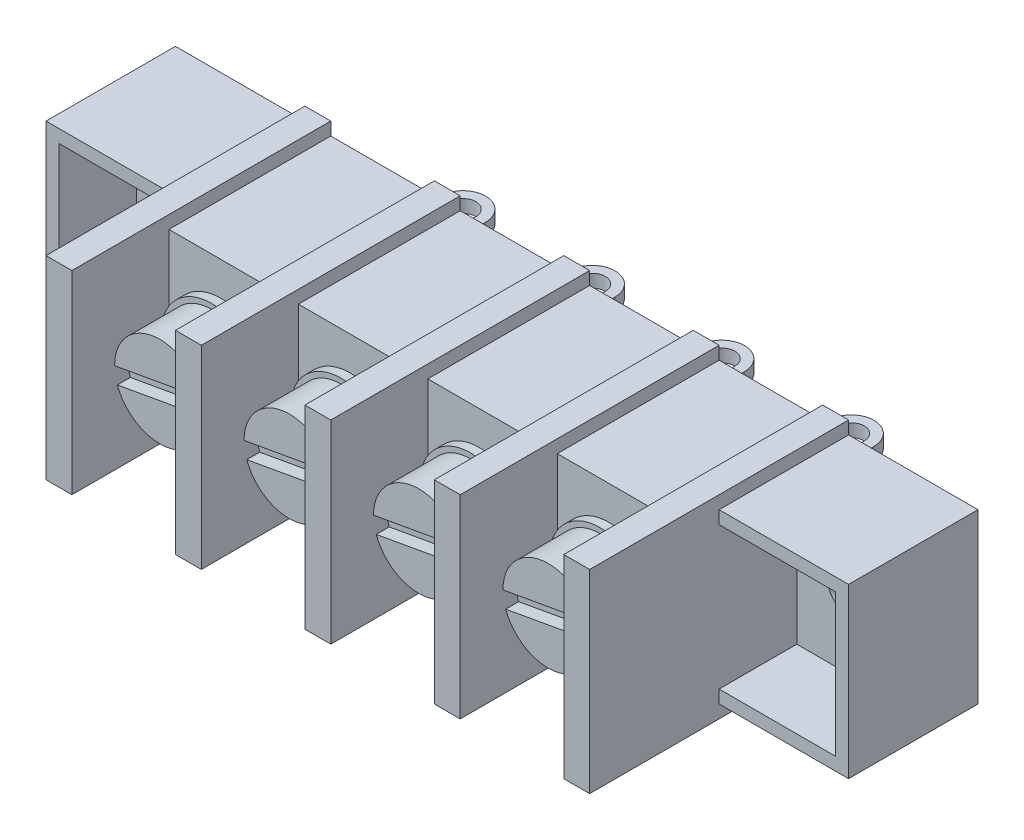
SolidWorks part; units mm, degrees
ref_plane "Спереди" through (0, 0, 0) normal (0, 0, 1) x (1, 0, 0)
ref_plane "Сверху" through (0, 0, 0) normal (0, 1, 0) x (1, 0, 0)
ref_plane "Справа" through (0, 0, 0) normal (1, 0, 0) x (0, 0, -1)
sketch "Эскиз1" plane through (0, 0, 0) normal (0, 0, 1) x (1, 0, 0)
  line L0 (-47.9787, 0) -> (44.4324, 0) construction
  line L1 (0, 0) -> (0, 38.9044) construction
  line L2 (-41, -7.5) -> (41, -7.5)
  line L3 (-41, -7.5) -> (-41, 7.5)
  line L4 (-41, 7.5) -> (41, 7.5)
  line L5 (41, -7.5) -> (41, 7.5)
  dimension "D1" = 15
  dimension "D2" = 82
extrude "Вытянуть1" add sketch "Эскиз1" along normal blind 10
sketch "Эскиз2" plane through (0, 0, 10) normal (0, 0, 1) x (1, 0, 0)
  line L0 (41, 7.5) -> (-41, 7.5) construction
  line L1 (-41, -7.5) -> (-39, -7.5)
  line L2 (-41, -7.5) -> (-41, 7.5)
  line L3 (-41, 7.5) -> (-39, 7.5)
  line L4 (-39, -7.5) -> (-39, 7.5)
  line L5 (0, 13.212) -> (0, -10.8914) construction
  line L6 (-41, -7.5) -> (41, -7.5) construction
  line L7 (-31, -7.5) -> (-29, -7.5)
  line L8 (-31, -7.5) -> (-31, 7.5)
  line L9 (-31, 7.5) -> (-29, 7.5)
  line L10 (-29, -7.5) -> (-29, 7.5)
  line L11 (-30, 8.3866) -> (-30, -8.2377) construction
  line L12 (1, 7.5) -> (-1, 7.5)
  line L13 (1, -7.5) -> (1, 7.5)
  line L14 (1, -7.5) -> (-1, -7.5)
  line L15 (-1, -7.5) -> (-1, 7.5)
  line L16 (29, -7.5) -> (29, 7.5)
  line L17 (31, 7.5) -> (29, 7.5)
  line L18 (31, -7.5) -> (31, 7.5)
  line L19 (31, -7.5) -> (29, -7.5)
  line L20 (39, -7.5) -> (39, 7.5)
  line L21 (41, 7.5) -> (39, 7.5)
  line L22 (41, -7.5) -> (41, 7.5)
  line L23 (41, -7.5) -> (39, -7.5)
  line L24 (-21, -7.5) -> (-19, -7.5)
  line L25 (-21, -7.5) -> (-21, 7.5)
  line L26 (-21, 7.5) -> (-19, 7.5)
  line L27 (-19, -7.5) -> (-19, 7.5)
  line L28 (9, -7.5) -> (9, 7.5)
  line L29 (-11, -7.5) -> (-9, -7.5)
  line L30 (-11, -7.5) -> (-11, 7.5)
  line L31 (-11, 7.5) -> (-9, 7.5)
  line L32 (-9, -7.5) -> (-9, 7.5)
  line L33 (11, 7.5) -> (9, 7.5)
  line L34 (-10, 8.3866) -> (-10, -8.2377) construction
  line L35 (-20, 8.3866) -> (-20, -8.2377) construction
  line L36 (11, -7.5) -> (11, 7.5)
  line L37 (11, -7.5) -> (9, -7.5)
  line L38 (19, -7.5) -> (19, 7.5)
  line L39 (21, 7.5) -> (19, 7.5)
  line L40 (21, -7.5) -> (21, 7.5)
  line L41 (21, -7.5) -> (19, -7.5)
  dimension "D1" = 2
  dimension "D2" = 10
  dimension "D3" = 2
  dimension "D4" = 8
extrude "Вытянуть2" add sketch "Эскиз2" along normal blind 10
sketch "Эскиз3" plane through (0, 0, 10) normal (0, 0, 1) x (1, 0, 0)
  line L0 (-35, 10.8914) -> (-35, -9.6255) construction
  line L3 (-31, 7.5) -> (-31, -7.5) construction
  line L4 (-39, -7.5) -> (-39, 7.5) construction
  line L5 (-39, -7.5) -> (-31, -7.5) construction
  line L6 (-39, -7.5) -> (-31, -7.5)
  line L7 (-39, -7.5) -> (-39, 7.5)
  line L8 (-39, 7.5) -> (-31, 7.5)
  line L9 (-31, -7.5) -> (-31, 7.5)
  line L10 (-31, 7.5) -> (-39, 7.5) construction
  line L13 (-21, -7.5) -> (-21, 7.5)
  line L14 (-21, 7.5) -> (-29, 7.5)
  line L15 (-21, -7.5) -> (-21, 7.5)
  line L16 (-29, -7.5) -> (-21, -7.5)
  line L17 (-29, 7.5) -> (-29, -7.5)
  line L18 (-21, 7.5) -> (-29, 7.5)
  line L19 (-29, 7.5) -> (-29, -7.5)
  line L20 (-29, -7.5) -> (-21, -7.5)
  line L25 (-11, -7.5) -> (-11, 7.5)
  line L26 (-11, 7.5) -> (-19, 7.5)
  line L27 (-19, 7.5) -> (-19, -7.5)
  line L28 (-19, -7.5) -> (-11, -7.5)
  line L33 (-9, 7.5) -> (-9, -7.5)
  line L34 (-9, -7.5) -> (-1, -7.5)
  line L35 (-1, -7.5) -> (-1, 7.5)
  line L36 (-1, 7.5) -> (-9, 7.5)
  line L42 (9, -7.5) -> (9, 7.5)
  line L43 (9, 7.5) -> (1, 7.5)
  line L44 (1, 7.5) -> (1, -7.5)
  line L45 (1, -7.5) -> (9, -7.5)
  line L50 (19, -7.5) -> (19, 7.5)
  line L51 (19, 7.5) -> (11, 7.5)
  line L52 (11, 7.5) -> (11, -7.5)
  line L53 (11, -7.5) -> (19, -7.5)
  line L58 (21, 7.5) -> (21, -7.5)
  line L59 (21, -7.5) -> (29, -7.5)
  line L60 (29, -7.5) -> (29, 7.5)
  line L61 (29, 7.5) -> (21, 7.5)
  line L66 (39, -7.5) -> (39, 7.5)
  line L67 (39, 7.5) -> (31, 7.5)
  line L68 (31, 7.5) -> (31, -7.5)
  line L69 (31, -7.5) -> (39, -7.5)
  dimension "D1" = 8
  dimension "D2" = 0
extrude "Вытянуть3" add sketch "Эскиз3" along normal blind 2.5
sketch "Эскиз4" plane through (0, 0, 12.5) normal (0, 0, 1) x (1, 0, 0)
  line L0 (-24.2616, 0) -> (23.4177, 0) construction
  line L1 (-35, 0) -> (-35, 16.4068) construction
  line L4 (0, 0) -> (0, 14.617) construction
  line L6 (-39, -7.5) -> (-39, 7.5) construction
  line L7 (-31, -7.5) -> (-31, 7.5) construction
  circle A0 centre (-35, 0) radius 3.9
  circle A1 centre (-25, 0) radius 3.9
  circle A2 centre (-15, 0) radius 3.9
  circle A3 centre (-5, 0) radius 3.9
  circle A4 centre (5, 0) radius 3.9
  circle A5 centre (15, 0) radius 3.9
  circle A6 centre (25, 0) radius 3.9
  circle A7 centre (35, 0) radius 3.9
  dimension "D1" = 7.8
  dimension "D2" = 10
extrude "Вытянуть4" add sketch "Эскиз4" along normal blind 0.7
sketch "Эскиз6" plane through (0, 0, 13.2) normal (0, 0, 1) x (1, 0, 0)
  line L0 (0, 0) -> (0, 15.7615) construction
  circle A0 centre (-35, 0) radius 3.5
  circle A1 centre (-35, 0) radius 3.9 construction
  circle A2 centre (-25, 0) radius 3.5
  circle A3 centre (-15, 0) radius 3.5
  circle A4 centre (-5, 0) radius 3.5
  circle A5 centre (5, 0) radius 3.5
  circle A6 centre (15, 0) radius 3.5
  circle A7 centre (25, 0) radius 3.5
  circle A8 centre (35, 0) radius 3.5
  circle A11 centre (5, 0) radius 3.5 [skipped]
  circle A12 centre (15, 0) radius 3.5 [skipped]
  circle A13 centre (25, 0) radius 3.5 [skipped]
  circle A14 centre (35, 0) radius 3.5 [skipped]
  dimension "D1" = 7
  dimension "D2" = 10
extrude "Вытянуть5" add sketch "Эскиз6" along normal blind 4
sketch "Эскиз7" plane through (0, 0, 17.2) normal (0, 0, 1) x (1, 0, 0)
  line L0 (-35, 0) -> (-19.4589, -11.6177) construction
  line L1 (-35, 0) -> (-12.9483, 3.9455) construction
  line L2 (-31.7114, 1.1979) -> (-38.5, -0.0167)
  line L3 (-31.5, 0.0167) -> (-38.2886, -1.1979)
  line L4 (-21.7114, 1.1979) -> (-28.5, -0.0167)
  line L5 (-21.5, 0.0167) -> (-28.2886, -1.1979)
  line L6 (-11.7114, 1.1979) -> (-18.5, -0.0167)
  line L7 (-11.5, 0.0167) -> (-18.2886, -1.1979)
  line L8 (-1.7114, 1.1979) -> (-8.5, -0.0167)
  line L9 (-1.5, 0.0167) -> (-8.2886, -1.1979)
  line L10 (0, 0) -> (0, 13.7349) construction
  line L11 (8.2886, 1.1979) -> (1.5, -0.0167)
  line L12 (8.5, 0.0167) -> (1.7114, -1.1979)
  line L13 (18.2886, 1.1979) -> (11.5, -0.0167)
  line L14 (18.5, 0.0167) -> (11.7114, -1.1979)
  line L15 (28.2886, 1.1979) -> (21.5, -0.0167)
  line L16 (28.5, 0.0167) -> (21.7114, -1.1979)
  line L17 (38.2886, 1.1979) -> (31.5, -0.0167)
  line L18 (38.5, 0.0167) -> (31.7114, -1.1979)
  circle A0 centre (-35, 0) radius 3.5 construction
  arc A1 (-31.5, 0.0167) -> (-31.7114, 1.1979) centre (-35, 0) ccw
  arc A2 (-38.5, -0.0167) -> (-38.2886, -1.1979) centre (-35, 0) ccw
  arc A3 (-21.5, 0.0167) -> (-21.7114, 1.1979) centre (-25, 0) ccw
  arc A4 (-28.5, -0.0167) -> (-28.2886, -1.1979) centre (-25, 0) ccw
  arc A5 (-11.5, 0.0167) -> (-11.7114, 1.1979) centre (-15, 0) ccw
  arc A6 (-18.5, -0.0167) -> (-18.2886, -1.1979) centre (-15, 0) ccw
  arc A7 (-1.5, 0.0167) -> (-1.7114, 1.1979) centre (-5, 0) ccw
  arc A8 (-8.5, -0.0167) -> (-8.2886, -1.1979) centre (-5, 0) ccw
  arc A9 (8.5, 0.0167) -> (8.2886, 1.1979) centre (5, 0) ccw
  arc A10 (1.5, -0.0167) -> (1.7114, -1.1979) centre (5, 0) ccw
  arc A11 (18.5, 0.0167) -> (18.2886, 1.1979) centre (15, 0) ccw
  arc A12 (11.5, -0.0167) -> (11.7114, -1.1979) centre (15, 0) ccw
  arc A13 (28.5, 0.0167) -> (28.2886, 1.1979) centre (25, 0) ccw
  arc A14 (21.5, -0.0167) -> (21.7114, -1.1979) centre (25, 0) ccw
  arc A15 (38.5, 0.0167) -> (38.2886, 1.1979) centre (35, 0) ccw
  arc A16 (31.5, -0.0167) -> (31.7114, -1.1979) centre (35, 0) ccw
  dimension "D2" = 1.2
extrude "Вырез-Вытянуть1" cut sketch "Эскиз7" against normal blind 1
sketch "Эскиз8" plane through (0, 0, 0) normal (0, 0, -1) x (-1, 0, 0)
  line L0 (-23.7342, 0) -> (23.7342, 0) construction
  line L1 (0, 12.8956) -> (0, -12.4209) construction
  line L2 (23.25, -0.5) -> (26.75, -0.5)
  line L3 (23.25, -0.5) -> (23.25, 0.5)
  line L4 (23.25, 0.5) -> (26.75, 0.5)
  line L5 (26.75, -0.5) -> (26.75, 0.5)
  line L6 (13.25, -0.5) -> (16.75, -0.5)
  line L7 (13.25, -0.5) -> (13.25, 0.5)
  line L8 (13.25, 0.5) -> (16.75, 0.5)
  line L9 (16.75, -0.5) -> (16.75, 0.5)
  line L10 (3.25, -0.5) -> (6.75, -0.5)
  line L11 (3.25, -0.5) -> (3.25, 0.5)
  line L12 (3.25, 0.5) -> (6.75, 0.5)
  line L13 (6.75, -0.5) -> (6.75, 0.5)
  line L14 (-6.75, -0.5) -> (-3.25, -0.5)
  line L15 (-6.75, -0.5) -> (-6.75, 0.5)
  line L16 (-6.75, 0.5) -> (-3.25, 0.5)
  line L17 (-3.25, -0.5) -> (-3.25, 0.5)
  line L18 (-16.75, -0.5) -> (-13.25, -0.5)
  line L19 (-16.75, -0.5) -> (-16.75, 0.5)
  line L20 (-16.75, 0.5) -> (-13.25, 0.5)
  line L21 (-13.25, -0.5) -> (-13.25, 0.5)
  line L22 (-26.75, -0.5) -> (-23.25, -0.5)
  line L23 (-26.75, -0.5) -> (-26.75, 0.5)
  line L24 (-26.75, 0.5) -> (-23.25, 0.5)
  line L25 (-23.25, -0.5) -> (-23.25, 0.5)
  line L26 (-36.75, -0.5) -> (-33.25, -0.5)
  line L27 (-36.75, -0.5) -> (-36.75, 0.5)
  line L28 (-36.75, 0.5) -> (-33.25, 0.5)
  line L29 (-33.25, -0.5) -> (-33.25, 0.5)
  line L47 (33.25, -0.5) -> (36.75, -0.5)
  line L48 (33.25, -0.5) -> (33.25, 0.5)
  line L49 (33.25, 0.5) -> (36.75, 0.5)
  line L50 (36.75, -0.5) -> (36.75, 0.5)
extrude "Вытянуть6" add sketch "Эскиз8" along normal blind 8
sketch "Эскиз10" plane through (-41, 0, 0) normal (-1, 0, 0) x (0, 0, 1)
  line L0 (10, -7.5) -> (10, 7.5)
  line L4 (0, 7.5) -> (0, -7.5)
  line L5 (0, -7.5) -> (20, -7.5)
  line L6 (20, -7.5) -> (20, 7.5)
  line L7 (20, 7.5) -> (0, 7.5)
  line L8 (0, 7.5) -> (0, -7.5)
  line L9 (0, -7.5) -> (10, -7.5)
  line L11 (10, 7.5) -> (0, 7.5)
  dimension "D2" = 10
  dimension "D1" = 0
extrude "Вытянуть7" add sketch "Эскиз10" along normal blind 10
sketch "Эскиз11" plane through (41, 0, 0) normal (1, 0, 0) x (0, 0, -1)
  line L4 (0, 7.5) -> (-10, 7.5)
  line L5 (0, -7.5) -> (0, 7.5)
  line L6 (-10, -7.5) -> (0, -7.5)
  line L7 (-10, 7.5) -> (-10, -7.5)
  line L8 (0, 7.5) -> (-10, 7.5)
  line L9 (0, -7.5) -> (0, 7.5)
  line L10 (-10, -7.5) -> (0, -7.5)
  line L11 (-10, 7.5) -> (-10, -7.5)
  dimension "D1" = 0
extrude "Вытянуть8" add sketch "Эскиз11" along normal blind 10
sketch "Эскиз12" plane through (0, 0, 10) normal (0, 0, 1) x (1, 0, 0)
  line L0 (-54.3833, 0) -> (55.0396, 0) construction
  line L1 (0, 0) -> (0, 16.7838) construction
  circle A0 centre (45, 0) radius 1.6
  circle A1 centre (-45, 0) radius 1.6
  dimension "D1" = 3.2
  dimension "D2" = 45
extrude "Вырез-Вытянуть2" cut sketch "Эскиз12" against normal blind 10
sketch "Эскиз13" plane through (0, 0, 10) normal (0, 0, 1) x (1, 0, 0)
  line L0 (41, 7.5) -> (41, -7.5) construction
  line L1 (41, -5.5) -> (50, -5.5)
  line L2 (41, -5.5) -> (41, 5.5)
  line L3 (41, 5.5) -> (50, 5.5)
  line L4 (50, -5.5) -> (50, 5.5)
  line L5 (51, 7.5) -> (51, -7.5) construction
  line L6 (51, 7.5) -> (41, 7.5) construction
  line L7 (51, -7.5) -> (41, -7.5) construction
  line L8 (0, 0) -> (0, 15.322) construction
  line L9 (-50, -5.5) -> (-50, 5.5)
  line L10 (-41, 5.5) -> (-50, 5.5)
  line L11 (-41, -5.5) -> (-41, 5.5)
  line L12 (-41, -5.5) -> (-50, -5.5)
  dimension "D1" = 1
  dimension "D2" = 2
  dimension "D3" = 2
extrude "Вырез-Вытянуть3" cut sketch "Эскиз13" against normal blind 6
sketch "Эскиз14" plane through (0, 0, 12.5) normal (0, 0, 1) x (1, 0, 0)
  line L0 (0, 0) -> (64.3223, 0) construction
  line L1 (0, 0) -> (0, 17.1529) construction
  line L2 (39, 7.5) -> (39, -7.5) construction
  line L3 (31, 7.5) -> (39, 7.5)
  line L4 (31, 7.5) -> (31, 6.5)
  line L5 (31, 6.5) -> (39, 6.5)
  line L6 (39, 7.5) -> (39, 6.5)
  line L7 (41, 7.5) -> (41, 5.5) construction
  line L8 (41, 6.5) -> (51, 6.5)
  line L9 (41, 6.5) -> (41, 7.5)
  line L10 (41, 7.5) -> (51, 7.5)
  line L11 (51, 6.5) -> (51, 7.5)
  line L12 (51, -6.5) -> (51, -7.5)
  line L13 (41, -7.5) -> (51, -7.5)
  line L14 (41, -6.5) -> (41, -7.5)
  line L15 (41, -6.5) -> (51, -6.5)
  line L16 (39, -7.5) -> (39, -6.5)
  line L17 (31, -6.5) -> (39, -6.5)
  line L18 (31, -7.5) -> (31, -6.5)
  line L19 (31, -7.5) -> (39, -7.5)
  line L20 (21, 7.5) -> (29, 7.5)
  line L21 (21, 7.5) -> (21, 6.5)
  line L22 (21, 6.5) -> (29, 6.5)
  line L23 (29, 7.5) -> (29, 6.5)
  line L24 (29, -7.5) -> (29, -6.5)
  line L25 (21, -6.5) -> (29, -6.5)
  line L26 (21, -7.5) -> (21, -6.5)
  line L27 (21, -7.5) -> (29, -7.5)
  line L28 (11, 7.5) -> (19, 7.5)
  line L29 (11, 7.5) -> (11, 6.5)
  line L30 (11, 6.5) -> (19, 6.5)
  line L31 (19, 7.5) -> (19, 6.5)
  line L32 (19, -7.5) -> (19, -6.5)
  line L33 (11, -6.5) -> (19, -6.5)
  line L34 (11, -7.5) -> (11, -6.5)
  line L35 (11, -7.5) -> (19, -7.5)
  line L36 (1, 7.5) -> (9, 7.5)
  line L37 (1, 7.5) -> (1, 6.5)
  line L38 (1, 6.5) -> (9, 6.5)
  line L39 (9, 7.5) -> (9, 6.5)
  line L40 (9, -7.5) -> (9, -6.5)
  line L41 (1, -6.5) -> (9, -6.5)
  line L42 (1, -7.5) -> (1, -6.5)
  line L43 (1, -7.5) -> (9, -7.5)
  line L44 (-9, 7.5) -> (-1, 7.5)
  line L45 (-9, 7.5) -> (-9, 6.5)
  line L46 (-9, 6.5) -> (-1, 6.5)
  line L47 (-1, 7.5) -> (-1, 6.5)
  line L48 (-1, -7.5) -> (-1, -6.5)
  line L49 (-9, -6.5) -> (-1, -6.5)
  line L50 (-9, -7.5) -> (-9, -6.5)
  line L51 (-9, -7.5) -> (-1, -7.5)
  line L52 (-19, 7.5) -> (-11, 7.5)
  line L53 (-19, 7.5) -> (-19, 6.5)
  line L54 (-19, 6.5) -> (-11, 6.5)
  line L55 (-11, 7.5) -> (-11, 6.5)
  line L56 (-11, -7.5) -> (-11, -6.5)
  line L57 (-19, -6.5) -> (-11, -6.5)
  line L58 (-19, -7.5) -> (-19, -6.5)
  line L59 (-19, -7.5) -> (-11, -7.5)
  line L60 (-29, 7.5) -> (-21, 7.5)
  line L61 (-29, 7.5) -> (-29, 6.5)
  line L62 (-29, 6.5) -> (-21, 6.5)
  line L63 (-21, 7.5) -> (-21, 6.5)
  line L64 (-21, -7.5) -> (-21, -6.5)
  line L65 (-29, -6.5) -> (-21, -6.5)
  line L66 (-29, -7.5) -> (-29, -6.5)
  line L67 (-29, -7.5) -> (-21, -7.5)
  line L68 (-39, 7.5) -> (-31, 7.5)
  line L69 (-39, 7.5) -> (-39, 6.5)
  line L70 (-39, 6.5) -> (-31, 6.5)
  line L71 (-31, 7.5) -> (-31, 6.5)
  line L72 (-31, -7.5) -> (-31, -6.5)
  line L73 (-39, -6.5) -> (-31, -6.5)
  line L74 (-39, -7.5) -> (-39, -6.5)
  line L75 (-39, -7.5) -> (-31, -7.5)
  line L76 (-41, -6.5) -> (-51, -6.5)
  line L77 (-41, -6.5) -> (-41, -7.5)
  line L78 (-41, -7.5) -> (-51, -7.5)
  line L79 (-51, -6.5) -> (-51, -7.5)
  line L80 (-51, 6.5) -> (-51, 7.5)
  line L81 (-41, 7.5) -> (-51, 7.5)
  line L82 (-41, 6.5) -> (-41, 7.5)
  line L83 (-41, 6.5) -> (-51, 6.5)
  dimension "D1" = 1
extrude "Вырез-Вытянуть4" cut sketch "Эскиз14" against normal blind 20
sketch "Эскиз15" plane through (0, -0.5, 0) normal (0, -1, 0) x (1, 0, 0)
  line L0 (33.25, -6.2124) -> (33.25, -10.5448)
  line L3 (33.25, -8) -> (33.25, 0) construction
  line L4 (33.25, -10.5448) -> (36.75, -10.5448)
  line L5 (34, -6.2124) -> (34, -5.8124)
  line L6 (36, -6.2124) -> (36, -5.8124)
  line L7 (36.75, -6.2124) -> (36.75, -10.5448)
  line L8 (36.75, -8) -> (36.75, 0) construction
  arc A0 (34, -6.2124) -> (36, -6.2124) centre (35, -6.2124) ccw
  arc A1 (34, -5.8124) -> (36, -5.8124) centre (35, -5.8124) cw
  arc A2 (33.25, -6.2124) -> (36.75, -6.2124) centre (35, -6.2124) ccw
  dimension "D1" = 2
extrude "Вырез-Вытянуть5" cut sketch "Эскиз15" against normal blind 20
pattern_linear "Линейный массив1" count 8 spacing 10 along (-1, 0, 0) of "Вырез-Вытянуть5"
sketch "Эскиз16" plane through (-41, 0, 0) normal (-1, 0, 0) x (0, 0, 1)
  line L12 (0, 6.5) -> (10, 6.5)
  line L13 (10, 6.5) -> (10, 5.5)
  line L14 (10, 5.5) -> (4, 5.5)
  line L15 (4, 5.5) -> (4, -5.5)
  line L16 (4, -5.5) -> (10, -5.5)
  line L17 (10, -5.5) -> (10, -6.5)
  line L18 (10, -6.5) -> (0, -6.5)
  line L19 (0, -6.5) -> (0, -7.5)
  line L20 (0, -7.5) -> (20, -7.5)
  line L21 (20, -7.5) -> (20, 7.5)
  line L22 (20, 7.5) -> (0, 7.5)
  line L23 (0, 7.5) -> (0, 6.5)
  line L24 (0, 6.5) -> (10, 6.5)
  line L25 (10, 6.5) -> (10, 5.5)
  line L26 (10, 5.5) -> (4, 5.5)
  line L27 (4, 5.5) -> (4, -5.5)
  line L28 (4, -5.5) -> (10, -5.5)
  line L29 (10, -5.5) -> (10, -6.5)
  line L30 (10, -6.5) -> (0, -6.5)
  line L31 (0, -6.5) -> (0, -7.5)
  line L32 (0, -7.5) -> (20, -7.5)
  line L33 (20, -7.5) -> (20, 7.5)
  line L34 (20, 7.5) -> (0, 7.5)
  line L35 (0, 7.5) -> (0, 6.5)
  dimension "D1" = 0
extrude "Вырез-Вытянуть6" cut sketch "Эскиз16" against normal up to surface (20 mm away) up to face at (-21, 0, 8.125)
sketch "Эскиз17" plane through (41, 0, 0) normal (1, 0, 0) x (0, 0, -1)
  line L12 (0, -6.5) -> (-10, -6.5)
  line L13 (-10, -6.5) -> (-10, -5.5)
  line L14 (-10, -5.5) -> (-4, -5.5)
  line L15 (-4, -5.5) -> (-4, 5.5)
  line L16 (-4, 5.5) -> (-10, 5.5)
  line L17 (-10, 5.5) -> (-10, 6.5)
  line L18 (-10, 6.5) -> (0, 6.5)
  line L19 (0, 6.5) -> (0, 7.5)
  line L20 (0, 7.5) -> (-20, 7.5)
  line L21 (-20, 7.5) -> (-20, -7.5)
  line L22 (-20, -7.5) -> (0, -7.5)
  line L23 (0, -7.5) -> (0, -6.5)
  line L24 (0, -6.5) -> (-10, -6.5)
  line L25 (-10, -6.5) -> (-10, -5.5)
  line L26 (-10, -5.5) -> (-4, -5.5)
  line L27 (-4, -5.5) -> (-4, 5.5)
  line L28 (-4, 5.5) -> (-10, 5.5)
  line L29 (-10, 5.5) -> (-10, 6.5)
  line L30 (-10, 6.5) -> (0, 6.5)
  line L31 (0, 6.5) -> (0, 7.5)
  line L32 (0, 7.5) -> (-20, 7.5)
  line L33 (-20, 7.5) -> (-20, -7.5)
  line L34 (-20, -7.5) -> (0, -7.5)
  line L35 (0, -7.5) -> (0, -6.5)
  dimension "D1" = 0
extrude "Вырез-Вытянуть7" cut sketch "Эскиз17" against normal up to surface (20 mm away) up to face at (21, 0, 8.125)
sketch "Эскиз18" plane through (0, -0.5, 0) normal (0, -1, 0) x (1, 0, 0)
  line L3 (-26.75, 0) -> (-26.75, -6.2124)
  line L4 (-23.25, -6.2124) -> (-23.25, 0)
  line L5 (-23.25, 0) -> (-26.75, 0)
  line L6 (-26.75, 0) -> (-26.75, -6.2124)
  line L7 (-23.25, -6.2124) -> (-23.25, 0)
  line L8 (-23.25, 0) -> (-26.75, 0)
  line L9 (-36.75, 0) -> (-36.75, -6.2124)
  line L10 (-33.25, -6.2124) -> (-33.25, 0)
  line L11 (-33.25, 0) -> (-36.75, 0)
  line L12 (-36.75, 0) -> (-36.75, -6.2124)
  line L13 (-33.25, -6.2124) -> (-33.25, 0)
  line L14 (-33.25, 0) -> (-36.75, 0)
  line L15 (23.25, 0) -> (23.25, -6.2124)
  line L16 (26.75, -6.2124) -> (26.75, 0)
  line L17 (26.75, 0) -> (23.25, 0)
  line L18 (23.25, 0) -> (23.25, -6.2124)
  line L19 (26.75, -6.2124) -> (26.75, 0)
  line L20 (26.75, 0) -> (23.25, 0)
  line L21 (33.25, 0) -> (33.25, -6.2124)
  line L22 (36.75, -6.2124) -> (36.75, 0)
  line L23 (36.75, 0) -> (33.25, 0)
  line L24 (33.25, 0) -> (33.25, -6.2124)
  line L25 (36.75, -6.2124) -> (36.75, 0)
  line L26 (36.75, 0) -> (33.25, 0)
  arc A1 (-26.75, -6.2124) -> (-23.25, -6.2124) centre (-25, -6.2124) ccw
  arc A2 (-26.75, -6.2124) -> (-23.25, -6.2124) centre (-25, -6.2124) ccw
  arc A3 (-36.75, -6.2124) -> (-33.25, -6.2124) centre (-35, -6.2124) ccw
  arc A4 (-36.75, -6.2124) -> (-33.25, -6.2124) centre (-35, -6.2124) ccw
  arc A5 (23.25, -6.2124) -> (26.75, -6.2124) centre (25, -6.2124) ccw
  arc A6 (23.25, -6.2124) -> (26.75, -6.2124) centre (25, -6.2124) ccw
  arc A7 (33.25, -6.2124) -> (36.75, -6.2124) centre (35, -6.2124) ccw
  arc A8 (33.25, -6.2124) -> (36.75, -6.2124) centre (35, -6.2124) ccw
  dimension "D1" = 0
  dimension "D2" = 0
  dimension "D3" = 0
  dimension "D4" = 0
extrude "Вырез-Вытянуть8" cut sketch "Эскиз18" against normal blind 10
sketch "Эскиз19" plane through (0, 0, 4) normal (0, 0, 1) x (1, 0, 0)
  line L0 (-45, 0) -> (45, 0) construction
  line L1 (0, 0) -> (0, 24.7801) construction
  circle A0 centre (-25, 0) radius 1.6
  circle A1 centre (25, 0) radius 1.6
  circle A2 centre (-45, 0) radius 1.6 construction
  dimension "D1" = 50
extrude "Вырез-Вытянуть9" cut sketch "Эскиз19" against normal blind 10
sketch "Эскиз20" plane through (0, 0, 4) normal (0, 0, 1) x (1, 0, 0)
  line L0 (-51, -6.5) -> (-21, -6.5) construction
  line L1 (-31, -6.5) -> (-30, -6.5)
  line L2 (-31, -6.5) -> (-31, 6.5)
  line L3 (-31, 6.5) -> (-30, 6.5)
  line L4 (-30, -6.5) -> (-30, 6.5)
  line L5 (-21, 6.5) -> (-51, 6.5) construction
  line L6 (0, 0) -> (0, 25.1465) construction
  line L7 (30, -6.5) -> (30, 6.5)
  line L8 (31, 6.5) -> (30, 6.5)
  line L9 (31, -6.5) -> (31, 6.5)
  line L10 (31, -6.5) -> (30, -6.5)
  circle A0 centre (-25, 0) radius 1.6 construction
  dimension "D1" = 1
  dimension "D2" = 6
extrude "Вытянуть9" add sketch "Эскиз20" along normal up to surface (6 mm away) up to face at (-35.75, 0, 10)
sketch "Эскиз21" plane through (-51, 0, 0) normal (-1, 0, 0) x (0, 0, 1)
  line L4 (10, 6.5) -> (0, 6.5)
  line L5 (0, 6.5) -> (0, -6.5)
  line L6 (0, -6.5) -> (10, -6.5)
  line L7 (10, -6.5) -> (10, 6.5)
  line L8 (10, 6.5) -> (0, 6.5)
  line L9 (0, 6.5) -> (0, -6.5)
  line L10 (0, -6.5) -> (10, -6.5)
  line L11 (10, -6.5) -> (10, 6.5)
  dimension "D1" = 0
extrude "Вырез-Вытянуть10" cut sketch "Эскиз21" against normal up to surface (20 mm away) up to face at (-31, 0, 7)
sketch "Эскиз22" plane through (51, 0, 0) normal (1, 0, 0) x (0, 0, -1)
  line L4 (-10, -6.5) -> (0, -6.5)
  line L5 (0, -6.5) -> (0, 6.5)
  line L6 (0, 6.5) -> (-10, 6.5)
  line L7 (-10, 6.5) -> (-10, -6.5)
  line L8 (-10, -6.5) -> (0, -6.5)
  line L9 (0, -6.5) -> (0, 6.5)
  line L10 (0, 6.5) -> (-10, 6.5)
  line L11 (-10, 6.5) -> (-10, -6.5)
  dimension "D1" = 0
extrude "Вырез-Вытянуть11" cut sketch "Эскиз22" against normal up to surface (20 mm away) up to face at (31, 0, 7)
